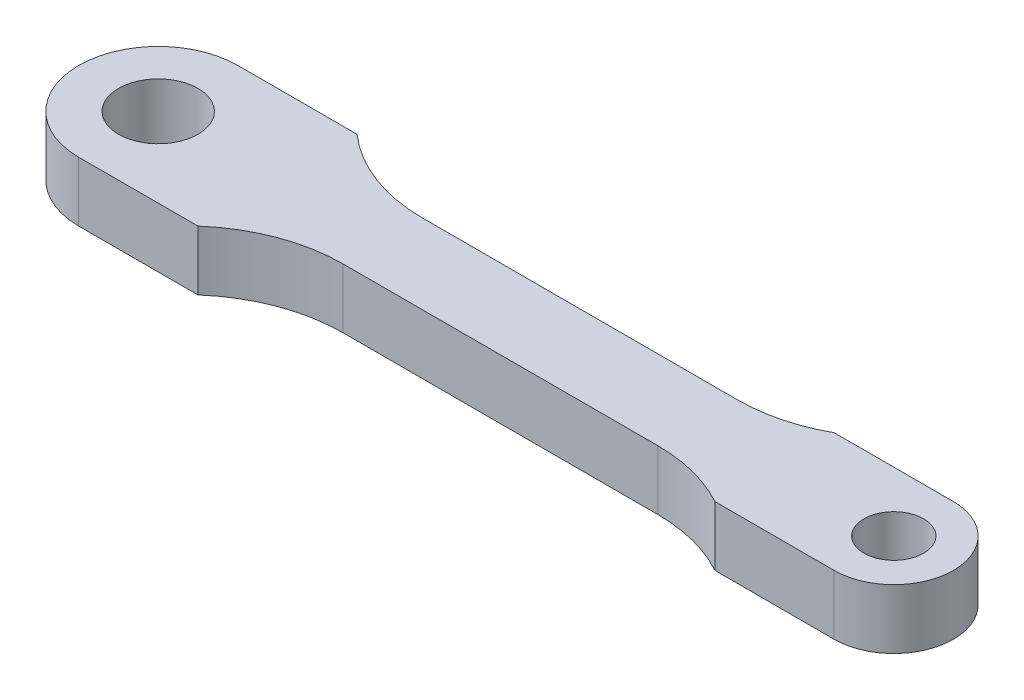
SolidWorks part; units mm, degrees
ref_plane "Ön Düzlem" through (0, 0, 0) normal (0, 0, 1) x (1, 0, 0)
ref_plane "Üst Düzlem" through (0, 0, 0) normal (0, 1, 0) x (1, 0, 0)
ref_plane "Sağ Düzlem" through (0, 0, 0) normal (1, 0, 0) x (0, 0, -1)
sketch "Sketch1" plane through (0, 0, 0) normal (0, 1, 0) x (1, 0, 0)
  line L0 (-18.5, 0) -> (18.5, 0) construction
  line L1 (-18.5, 4) -> (-12.5, 4)
  line L2 (-18.5, -4) -> (-12.5, -4)
  line L3 (18.5, 3) -> (12.5, 3)
  line L4 (18.5, -3) -> (12.5, -3)
  line L5 (-7.2085, 2) -> (8.627, 2)
  line L6 (-7.2085, -2) -> (8.627, -2)
  circle A0 centre (-18.5, 0) radius 4
  circle A1 centre (18.5, 0) radius 3
  arc A2 (12.5, 3) -> (8.627, 2) centre (8.627, 10) cw
  arc A3 (12.5, -3) -> (8.627, -2) centre (8.627, -10) ccw
  arc A4 (-12.5, 4) -> (-7.2085, 2) centre (-7.2085, 10) ccw
  arc A5 (-12.5, -4) -> (-7.2085, -2) centre (-7.2085, -10) cw
  circle A6 centre (-18.5, 0) radius 2
  circle A7 centre (18.5, 0) radius 1.5
  dimension "D1" = 37
  dimension "D3" = 8
  dimension "D4" = 6
  dimension "D2" = 4
  dimension "D5" = 6
  dimension "D6" = 6
extrude "Boss-Extrude1" add sketch "Sketch1" along normal mid plane 3
scale "Scale1" scale about centroid uniform scaling yes scale factor 1.5
